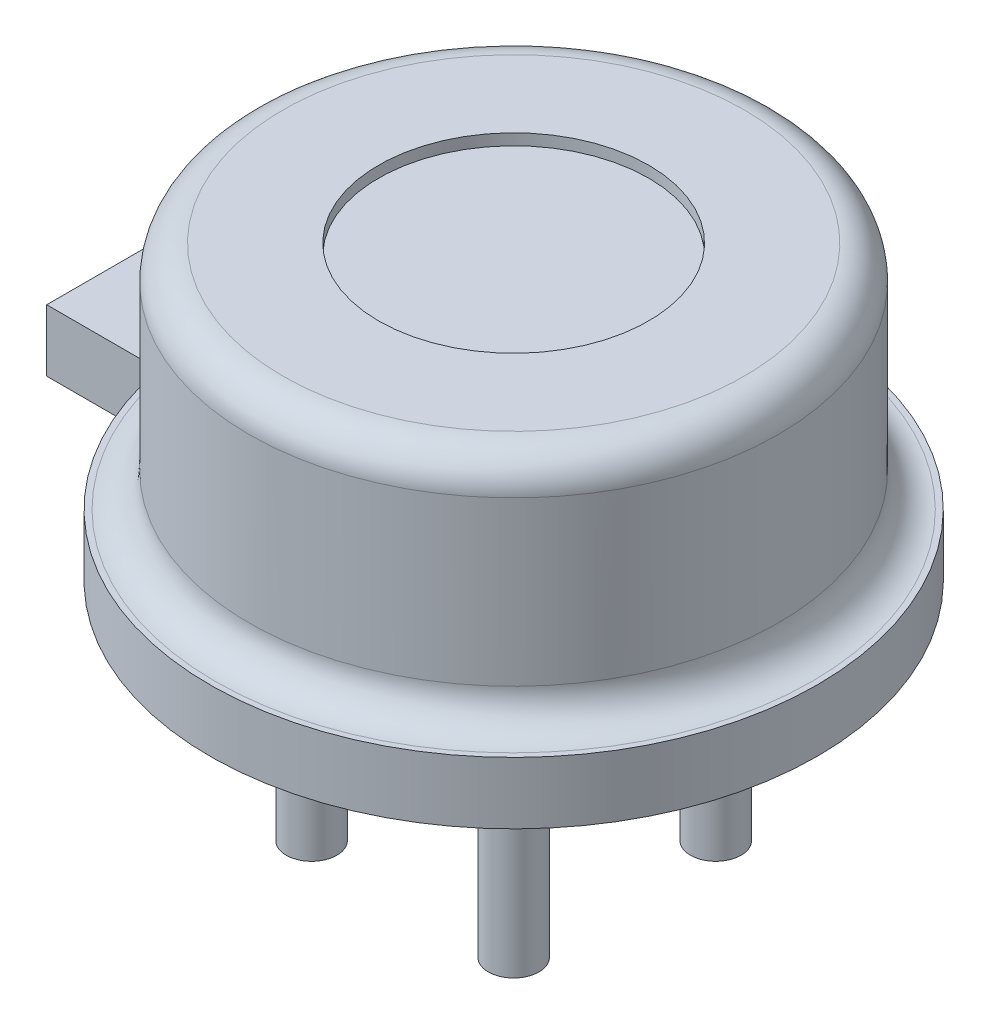
SolidWorks part; units mm, degrees
ref_plane "Front Plane" through (0, 0, 0) normal (0, 0, 1) x (1, 0, 0)
ref_plane "Top Plane" through (0, 0, 0) normal (0, 1, 0) x (1, 0, 0)
ref_plane "Right Plane" through (0, 0, 0) normal (1, 0, 0) x (0, 0, -1)
sketch "Sketch1" plane through (0, 0, 0) normal (0, 1, 0) x (1, 0, 0)
  circle A0 centre (0, 0) radius 2.35
  dimension "D1" = 4.7
extrude "Boss-Extrude1" add sketch "Sketch1" along normal blind 2.6
sketch "Sketch2" plane through (0, 0, 0) normal (0, -1, 0) x (1, 0, 0)
  circle A0 centre (0, 0) radius 2.7
  dimension "D1" = 5.4
extrude "Boss-Extrude2" add sketch "Sketch2" against normal blind 0.55
fillet "Fillet1" radius 0.3 1 edges at (0, 0.55, -2.35)
fillet "Fillet2" radius 0.3 1 edges at (0, 2.6, 2.35)
sketch "Sketch3" plane through (0, 2.6, 0) normal (0, 1, 0) x (1, 0, 0)
  circle A0 centre (0, 0) radius 1.2
  dimension "D1" = 2.4
extrude "Cut-Extrude1" cut sketch "Sketch3" against normal blind 0.1
sketch "Sketch4" plane through (0, 0, 0) normal (0, -1, 0) x (1, 0, 0)
  line L1 (-2.5, 0.5) -> (-3.65, 0.5)
  line L2 (-2.5, 0.5) -> (-2.5, -0.5)
  line L3 (-2.5, -0.5) -> (-3.65, -0.5)
  line L4 (-3.65, 0.5) -> (-3.65, -0.5)
  dimension "D1" = 1
  dimension "D2" = 0.5
  dimension "D3" = 2.5
  dimension "D4" = 1.15
extrude "Boss-Extrude3" add sketch "Sketch4" against normal up to surface (0.55 mm away) up to face at (0, 0.55, -2.65)
sketch "Sketch5" plane through (0, 0, 0) normal (0, -1, 0) x (1, 0, 0)
  circle A0 centre (-0.898, 0.898) radius 0.225
  circle A1 centre (0.898, 0.898) radius 0.225
  circle A2 centre (-0.898, -0.898) radius 0.225
  circle A3 centre (0.898, -0.898) radius 0.225
  dimension "D1" = 0.45
  dimension "D2" = 0.45
  dimension "D3" = 0.45
  dimension "D4" = 0.45
  dimension "D5" = 1.27
  dimension "D6" = 1.27
  dimension "D7" = 1.27
  dimension "D8" = 1.27
extrude "Boss-Extrude4" add sketch "Sketch5" along normal blind 2
